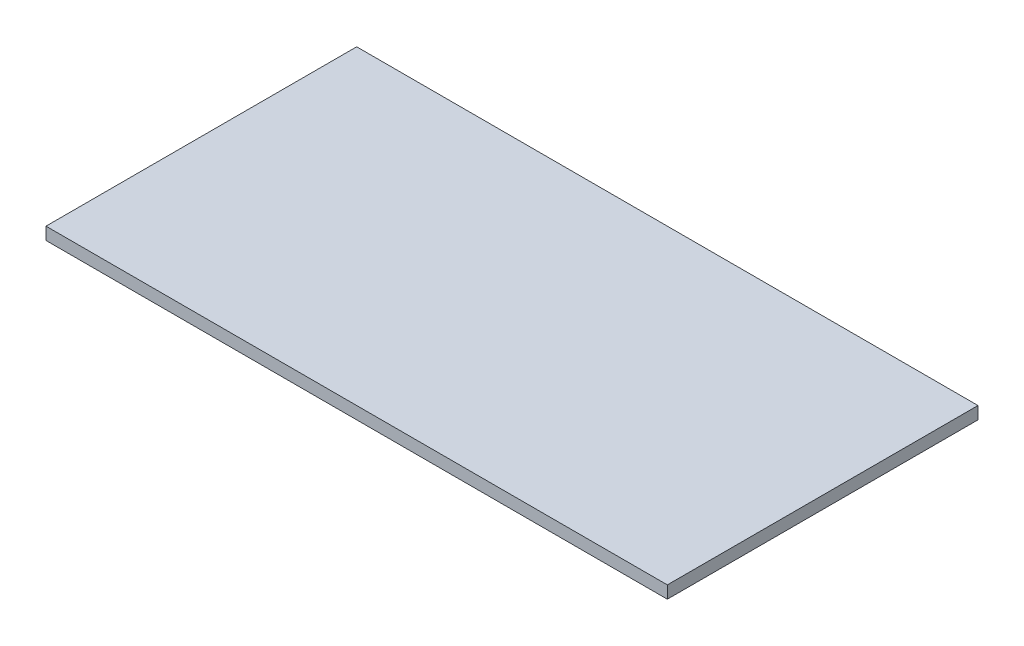
SolidWorks part; units mm, degrees
ref_plane "Front Plane" through (0, 0, 0) normal (0, 0, 1) x (1, 0, 0)
ref_plane "Top Plane" through (0, 0, 0) normal (0, 1, 0) x (1, 0, 0)
ref_plane "Right Plane" through (0, 0, 0) normal (1, 0, 0) x (0, 0, -1)
sketch "Sketch2" plane through (0, 0, 0) normal (0, 1, 0) x (1, 0, 0)
  line L1 (40, -20) -> (-40, -20)
  line L2 (40, -20) -> (40, 20)
  line L3 (40, 20) -> (-40, 20)
  line L4 (-40, -20) -> (-40, 20)
  line L5 (40, -20) -> (-40, 20) construction
  line L6 (40, 20) -> (-40, -20) construction
  point P1 (0, 0)
  point P6 (0, 0)
  point P7 (0, 0)
  dimension "D1" = 80
  dimension "D2" = 40
extrude "Boss-Extrude1" add sketch "Sketch2" along normal blind 1.6
